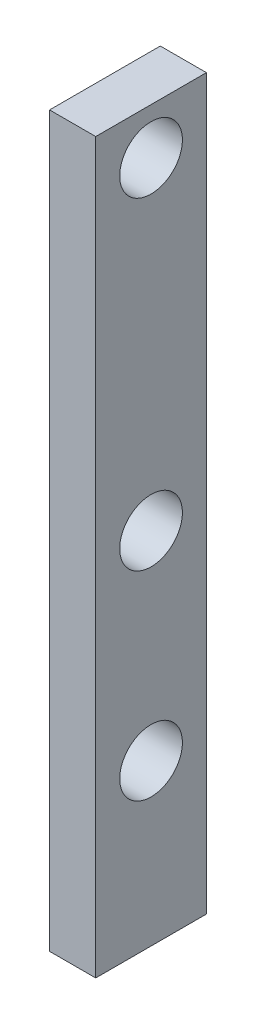
SolidWorks part; units mm, degrees
ref_plane "Front Plane" through (0, 0, 0) normal (0, 0, 1) x (1, 0, 0)
ref_plane "Top Plane" through (0, 0, 0) normal (0, 1, 0) x (1, 0, 0)
ref_plane "Right Plane" through (0, 0, 0) normal (1, 0, 0) x (0, 0, -1)
sketch "Sketch2" plane through (0, 0, 0) normal (1, 0, 0) x (0, 0, -1)
  line L0 (3, 0) -> (3, 39.5) construction
  line L1 (0, 0) -> (6, 0)
  line L2 (0, 0) -> (0, 39.5)
  line L3 (0, 39.5) -> (6, 39.5)
  line L4 (6, 0) -> (6, 39.5)
  circle A0 centre (3, 8.7) radius 1.7
  circle A1 centre (3, 19.5) radius 1.7
  circle A2 centre (3, 37) radius 1.7
  point P13 (6.5367, 37.0552)
  point P14 (2.9691, 32.3963)
  dimension "D1" = 17.5
  dimension "D3" = 3.4
  dimension "D2" = 10.8
  dimension "D4" = 6
  dimension "D5" = 39.5
  dimension "D6" = 8.7
extrude "Boss-Extrude1" add sketch "Sketch2" along normal blind 2.5
